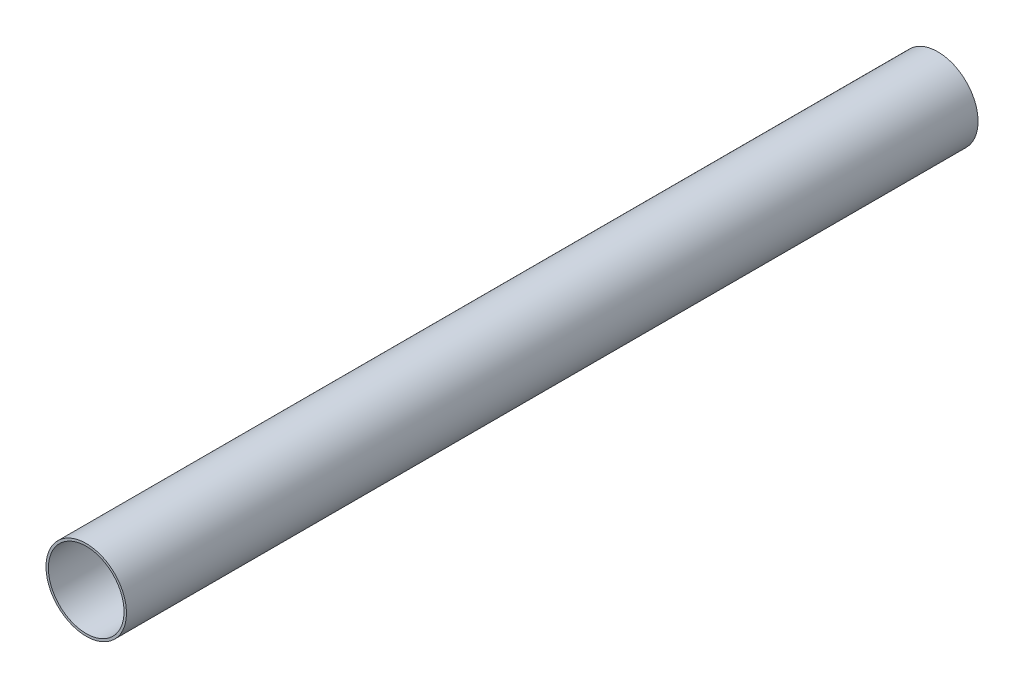
SolidWorks part; units mm, degrees
material "Carbon fiber"
ref_plane "Ön Düzlem" through (0, 0, 0) normal (0, 0, 1) x (1, 0, 0)
ref_plane "Üst Düzlem" through (0, 0, 0) normal (0, 1, 0) x (1, 0, 0)
ref_plane "Sağ Düzlem" through (0, 0, 0) normal (1, 0, 0) x (0, 0, -1)
sketch "Sketch1" plane through (0, 0, 0) normal (0, 0, 1) x (1, 0, 0)
  circle A0 centre (0, 0) radius 8
  circle A1 centre (0, 0) radius 8.5
  dimension "D1" = 16
  dimension "D2" = 17
extrude "Boss-Extrude1" add sketch "Sketch1" along normal blind 180
equation "\"DD_ArmLengthMm\"= 180"
equation "\"DD_ArmOdMm\"= 17"
equation "\"DD_ArmIdMm\"= 16"
equation "\"D1@Sketch1\"=\"DD_ArmIdMm\""
equation "\"D2@Sketch1\"=\"DD_ArmOdMm\""
equation "\"D1@Boss-Extrude1\"=\"DD_ArmLengthMm\""
